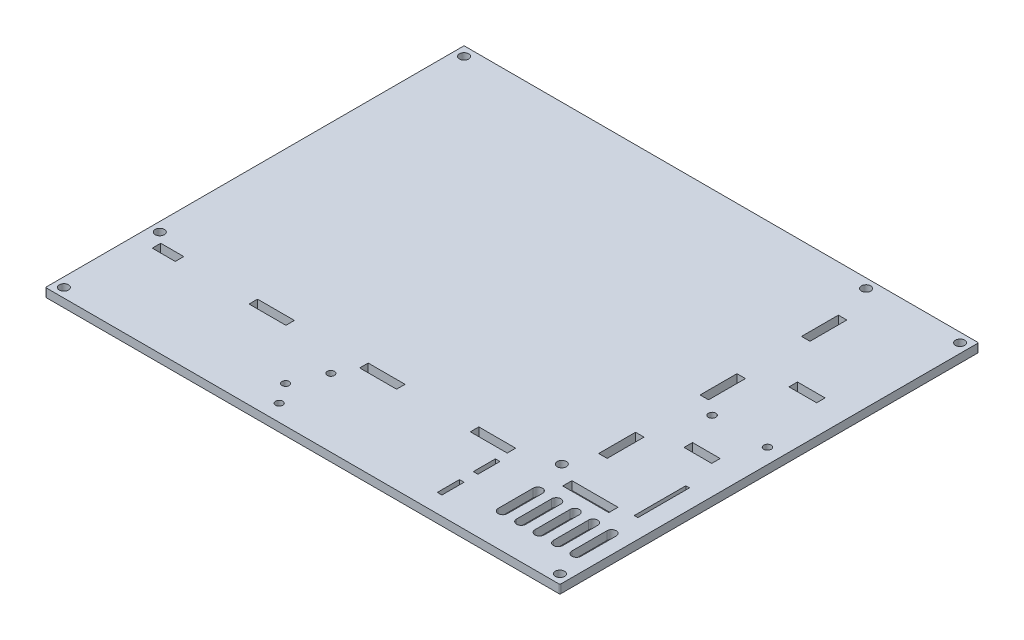
SolidWorks part; units mm, degrees
material "Acrylic (Medium-high impact)"
ref_plane "Front Plane" through (0, 0, 0) normal (0, 0, 1) x (1, 0, 0)
ref_plane "Top Plane" through (0, 0, 0) normal (0, 1, 0) x (1, 0, 0)
ref_plane "Right Plane" through (0, 0, 0) normal (1, 0, 0) x (0, 0, -1)
sketch "Sketch1" plane through (0, 0, 0) normal (0, 1, 0) x (1, 0, 0)
  line L0 (134.5, 108.5) -> (83.5, 108.5) construction
  line L1 (-140.5, -114.5) -> (140.5, -114.5)
  line L2 (-140.5, -114.5) -> (-140.5, 114.5)
  line L3 (-140.5, 114.5) -> (140.5, 114.5)
  line L4 (140.5, -114.5) -> (140.5, 114.5)
  line L5 (-140.5, -114.5) -> (140.5, 114.5) construction
  line L6 (-140.5, 114.5) -> (140.5, -114.5) construction
  line L7 (83.5, 108.5) -> (-134.5, 108.5) construction
  line L8 (134.5, 108.5) -> (134.5, -108.5) construction
  line L9 (83.5, -56.5) -> (83.5, 108.5) construction
  line L10 (83.5, -56.5) -> (-134.5, -56.5) construction
  line L11 (-134.5, 108.5) -> (-134.5, -56.5) construction
  line L12 (-56.5, -63.8) -> (43.5, -63.8) construction
  line L13 (131.3, 55.955) -> (131.3, -28.699) construction
  line L14 (-129, -61.5) -> (-116.5, -61.5)
  line L15 (-129, -61.5) -> (-129, -66.1)
  line L16 (-129, -66.1) -> (-116.5, -66.1)
  line L17 (-116.5, -61.5) -> (-116.5, -66.1)
  line L18 (101.3, 7.23) -> (131.3, 7.23) construction
  line L19 (108.8, 46) -> (123.8, 46)
  line L20 (108.8, 46) -> (108.8, 41.4)
  line L21 (108.8, 41.4) -> (123.8, 41.4)
  line L22 (123.8, 46) -> (123.8, 41.4)
  line L23 (108.8, -10.9) -> (123.8, -10.9)
  line L24 (108.8, -10.9) -> (108.8, -15.5)
  line L25 (93.1, -41.5) -> (88.5, -41.5)
  line L26 (108.8, -15.5) -> (123.8, -15.5)
  line L27 (93.1, -41.5) -> (93.1, -21.5)
  line L28 (93.1, -21.5) -> (88.5, -21.5)
  line L29 (88.5, -41.5) -> (88.5, -21.5)
  line L30 (93.1, 68.5) -> (88.5, 68.5)
  line L31 (93.1, 68.5) -> (93.1, 88.5)
  line L32 (93.1, 88.5) -> (88.5, 88.5)
  line L33 (88.5, 68.5) -> (88.5, 88.5)
  line L34 (-76.5, -66.1) -> (-56.5, -66.1)
  line L35 (-76.5, -66.1) -> (-76.5, -61.5)
  line L36 (-76.5, -61.5) -> (-56.5, -61.5)
  line L37 (-56.5, -66.1) -> (-56.5, -61.5)
  line L38 (43.5, -66.1) -> (63.5, -66.1)
  line L39 (43.5, -66.1) -> (43.5, -61.5)
  line L40 (43.5, -61.5) -> (63.5, -61.5)
  line L41 (63.5, -66.1) -> (63.5, -61.5)
  line L42 (123.8, -10.9) -> (123.8, -15.5)
  line L43 (-25.5, 108.5) -> (-25.5, -114.5) construction
  line L51 (90.8, -21.5) -> (90.8, 13.5) construction
  line L52 (93.1, 13.5) -> (88.5, 13.5)
  line L53 (93.1, 13.5) -> (93.1, 33.5)
  line L54 (93.1, 33.5) -> (88.5, 33.5)
  line L55 (88.5, 13.5) -> (88.5, 33.5)
  line L56 (90.8, 33.5) -> (90.8, 68.5) construction
  line L58 (-16.5, -61.5) -> (3.5, -61.5)
  line L59 (-16.5, -61.5) -> (-16.5, -66.1)
  line L60 (-16.5, -66.1) -> (3.5, -66.1)
  line L61 (3.5, -61.5) -> (3.5, -66.1)
  circle A0 centre (-134.5, 108.5) radius 2.5
  circle A1 centre (134.5, 108.5) radius 2.5
  circle A2 centre (83.5, 108.5) radius 2.5
  circle A3 centre (134.5, -108.5) radius 2.5
  circle A4 centre (83.5, -56.5) radius 2.5
  circle A5 centre (-134.5, -56.5) radius 2.5
  circle A6 centre (101.3, 7.23) radius 2
  circle A7 centre (-134.5, -108.5) radius 2.5
  circle A8 centre (131.3, 7.23) radius 2
  circle A9 centre (-21.75, -104.5) radius 1.95
  circle A10 centre (-29.25, -93.5) radius 1.95
  circle A11 centre (-21.75, -76.5) radius 1.95
  point P0 (0, 0)
  point P67 (-6.5, -63.8)
  point P91 (-6.5, -66.1)
  dimension "D3" = 5
  dimension "D10" = 11.5
  dimension "D12" = 12.5
  dimension "D14" = 4.6
  dimension "D37" = 53
  dimension "D42" = 3.75
  dimension "D21" = 4
  dimension "D23" = 30
  dimension "D39" = 3.9
  dimension "D40" = 3.9
  dimension "D44" = 3.9
  dimension "D1" = 229
  dimension "D2" = 281
  dimension "D4" = 6
  dimension "D5" = 51
  dimension "D6" = 6
  dimension "D7" = 6
  dimension "D8" = 165
  dimension "D9" = 6
  dimension "D11" = 15
  dimension "D13" = 47.4
  dimension "D15" = 4.6
  dimension "D16" = 20
  dimension "D17" = 4.6
  dimension "D18" = 40
  dimension "D19" = 40
  dimension "D20" = 52.3
  dimension "D22" = 18.13
  dimension "D24" = 34.17
  dimension "D25" = 9.2
  dimension "D26" = 90
  dimension "D27" = 26
  dimension "D28" = 52
  dimension "D29" = 20
  dimension "D30" = 4.6
  dimension "D31" = 10
  dimension "D32" = 100
  dimension "D33" = 134
  dimension "D34" = 107.27
  dimension "D35" = 68.5
  dimension "D36" = 7.5
  dimension "D38" = 3.75
  dimension "D41" = 21
  dimension "D43" = 38
  dimension "D45" = 3.75
extrude "Boss-Extrude1" add sketch "Sketch1" along normal blind 4.6
sketch "Sketch2" plane through (0, 4.6, 0) normal (0, 1, 0) x (1, 0, 0)
  line L0 (-139.5, 113.5) -> (139.5, 113.5)
  line L1 (-140.5, 114.5) -> (140.5, 114.5)
  line L2 (-140.5, 114.5) -> (-140.5, -114.5)
  line L3 (-140.5, -114.5) -> (140.5, -114.5)
  line L4 (140.5, 114.5) -> (140.5, -114.5)
  line L5 (139.5, 113.5) -> (139.5, -113.5)
  line L6 (-139.5, -113.5) -> (139.5, -113.5)
  line L7 (-139.5, 113.5) -> (-139.5, -113.5)
  dimension "D1" = 1
extrude "Cut-Extrude1" cut sketch "Sketch2" against normal through all
sketch "Sketch3" plane through (0, 0, 0) normal (0, -1, 0) x (1, 0, 0)
  line L0 (139.5, 113.5) -> (139.5, -113.5) construction
  line L1 (119, 61.5) -> (94, 61.5)
  line L2 (119, 61.5) -> (119, 66.5)
  line L3 (119, 66.5) -> (94, 66.5)
  line L4 (94, 61.5) -> (94, 66.5)
  line L5 (-139.5, 113.5) -> (139.5, 113.5) construction
  dimension "D1" = 20.5
  dimension "D2" = 25
  dimension "D3" = 47
  dimension "D4" = 5
extrude "Cut-Extrude2" cut sketch "Sketch3" against normal through all
sketch "Sketch6" plane through (0, 4.6, 0) normal (0, 1, 0) x (1, 0, 0)
  line L0 (-139.5, -113.5) -> (139.5, -113.5) construction
  line L1 (63, -72) -> (65.5, -72)
  line L2 (63, -72) -> (63, -84)
  line L3 (63, -84) -> (65.5, -84)
  line L4 (65.5, -72) -> (65.5, -84)
  line L5 (63, -91.5) -> (65.5, -91.5)
  line L6 (63, -91.5) -> (63, -103.5)
  line L7 (63, -103.5) -> (65.5, -103.5)
  line L8 (65.5, -91.5) -> (65.5, -103.5)
  line L10 (139.5, -113.5) -> (139.5, 113.5) construction
  dimension "D1" = 2.5
  dimension "D2" = 12
  dimension "D3" = 10
  dimension "D4" = 7.5
  dimension "D5" = 74
extrude "Cut-Extrude5" cut sketch "Sketch6" against normal through all
sketch "Sketch5" plane through (0, 0, 0) normal (0, 1, 0) x (1, 0, 0)
  line L0 (129.5, -75.5) -> (129.5, -94.5) construction
  line L1 (132, -75.5) -> (132, -94.5)
  line L2 (127, -75.5) -> (127, -94.5)
  line L3 (119.5, -75.5) -> (119.5, -94.5) construction
  line L4 (122, -75.5) -> (122, -94.5)
  line L5 (117, -75.5) -> (117, -94.5)
  line L6 (109.5, -75.5) -> (109.5, -94.5) construction
  line L7 (112, -75.5) -> (112, -94.5)
  line L8 (107, -75.5) -> (107, -94.5)
  line L9 (119, -66.5) -> (94, -66.5) construction
  line L10 (99.5, -75.5) -> (99.5, -94.5) construction
  line L11 (102, -75.5) -> (102, -94.5)
  line L12 (97, -75.5) -> (97, -94.5)
  line L13 (89.5, -75.5) -> (89.5, -94.5) construction
  line L14 (92, -75.5) -> (92, -94.5)
  line L15 (87, -75.5) -> (87, -94.5)
  line L16 (-139.5, -113.5) -> (139.5, -113.5) construction
  arc A0 (132, -75.5) -> (127, -75.5) centre (129.5, -75.5) ccw
  arc A1 (127, -94.5) -> (132, -94.5) centre (129.5, -94.5) ccw
  arc A2 (122, -75.5) -> (117, -75.5) centre (119.5, -75.5) ccw
  arc A3 (117, -94.5) -> (122, -94.5) centre (119.5, -94.5) ccw
  arc A4 (112, -75.5) -> (107, -75.5) centre (109.5, -75.5) ccw
  arc A5 (107, -94.5) -> (112, -94.5) centre (109.5, -94.5) ccw
  circle A6 centre (134.5, -108.5) radius 2.5 construction
  arc A7 (102, -75.5) -> (97, -75.5) centre (99.5, -75.5) ccw
  arc A8 (97, -94.5) -> (102, -94.5) centre (99.5, -94.5) ccw
  arc A9 (92, -75.5) -> (87, -75.5) centre (89.5, -75.5) ccw
  arc A10 (87, -94.5) -> (92, -94.5) centre (89.5, -94.5) ccw
  point P2 (129.5, -85)
  point P7 (119.5, -85)
  point P14 (109.5, -85)
  point P27 (99.5, -85)
  point P34 (89.5, -85)
  dimension "D1" = 5
  dimension "D2" = 19
  dimension "D3" = 9
  dimension "D4" = 5
  dimension "D5" = 10
  dimension "D6" = 10
  dimension "D7" = 10
  dimension "D8" = 10
  dimension "D9" = 19
extrude "Cut-Extrude4" cut sketch "Sketch5" along normal through all
sketch "Sketch8" plane through (0, 4.6, 0) normal (0, 1, 0) x (1, 0, 0)
  line L0 (129.1, -61.0001) -> (127.4289, -61.0001) construction
  line L1 (127.4289, -61.0001) -> (129.1, -61.0001) construction
  line L2 (127.4289, -61.0001) -> (127.4289, -33.0001) construction
  line L3 (127.4289, -33.0001) -> (129.1, -33.0001) construction
  line L4 (129.1, -61.0001) -> (129.1, -33.0001) construction
  line L5 (129.1, -33.0001) -> (129.1, -61.0001) construction
  line L6 (127.4289, -61.0001) -> (127.4289, -33.0001) construction
  line L7 (129.1, -33.0001) -> (127.4289, -33.0001) construction
  line L8 (128.2644, -61.0001) -> (128.2644, -60.1495) construction
  line L9 (127.2644, -33.0001) -> (129.2644, -33.0001)
  line L10 (127.2644, -33.0001) -> (127.2644, -61.0001)
  line L11 (127.2644, -61.0001) -> (129.2644, -61.0001)
  line L12 (129.2644, -33.0001) -> (129.2644, -61.0001)
  dimension "D1" = 1.6711
  dimension "D2" = 2
extrude "Cut-Extrude7" cut sketch "Sketch8" against normal through all
fillet "Fillet2" radius 0.5 4 edges at (139.5, 2.3, 113.5) (-139.5, 2.3, 113.5) (139.5, 2.3, -113.5) (-139.5, 2.3, -113.5)
